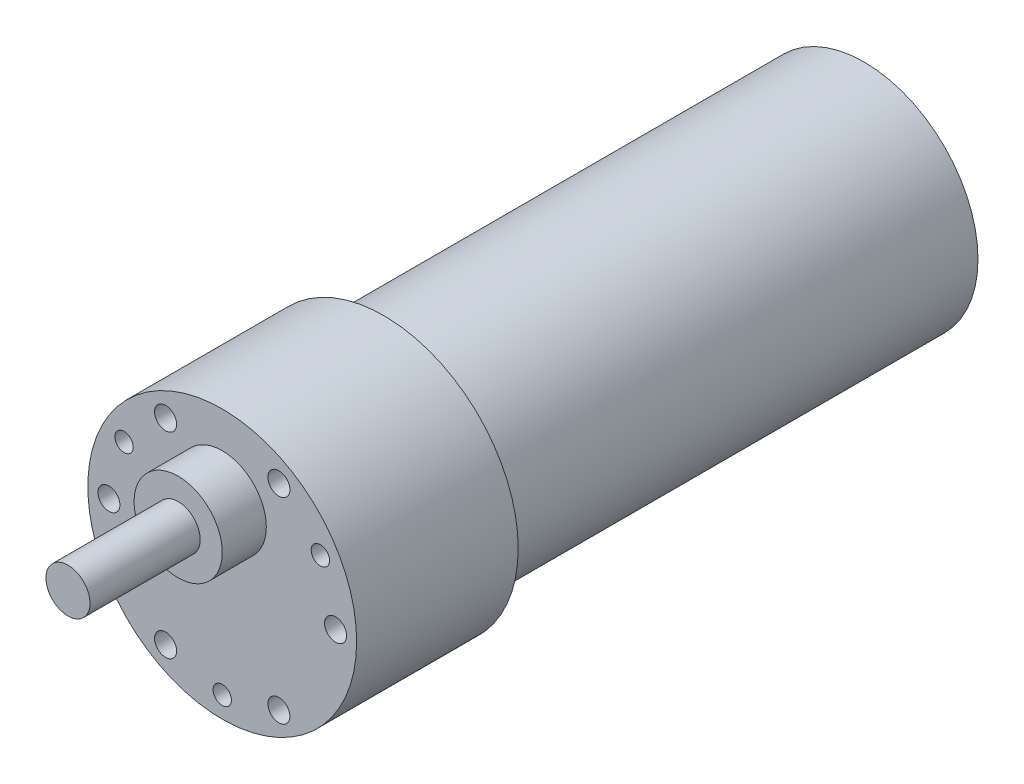
SolidWorks part; units mm, degrees
ref_plane "Alzado" through (0, 0, 0) normal (0, 0, 1) x (1, 0, 0)
ref_plane "Planta" through (0, 0, 0) normal (0, 1, 0) x (1, 0, 0)
ref_plane "Vista lateral" through (0, 0, 0) normal (1, 0, 0) x (0, 0, -1)
sketch "Croquis1" plane through (0, 0, 0) normal (0, 0, 1) x (1, 0, 0)
  circle A0 centre (0, 0) radius 15.5
  dimension "D1" = 31
extrude "Saliente-Extruir1" add sketch "Croquis1" along normal blind 65.4
sketch "Croquis2" plane through (0, 0, 0) normal (0, 0, -1) x (-1, 0, 0)
  circle A0 centre (0, 0) radius 6
  dimension "D1" = 12
extrude "Saliente-Extruir2" add sketch "Croquis2" along normal blind 2
sketch "Croquis3" plane through (0, 0, 65.4) normal (0, 0, 1) x (1, 0, 0)
  circle A0 centre (0, 0) radius 18.3
  dimension "D1" = 36.6
extrude "Saliente-Extruir3" add sketch "Croquis3" along normal blind 22
sketch "Croquis4" plane through (0, 0, 87.4) normal (0, 0, 1) x (1, 0, 0)
  circle A0 centre (0, 0) radius 16.93
  circle A1 centre (0, 0) radius 18.3 construction
  circle A2 centre (-15.43, 0) radius 1.5
  circle A3 centre (-7.715, 13.3628) radius 1.5
  circle A4 centre (7.715, 13.3628) radius 1.5
  circle A5 centre (15.43, 0) radius 1.5
  circle A6 centre (7.715, -13.3628) radius 1.5
  circle A7 centre (-7.715, -13.3628) radius 1.5
  point P19 (0, 0)
  dimension "D1" = 1.37
  dimension "D2" = 3
  dimension "D3" = 6
extrude "Cortar-Extruir1" cut sketch "Croquis4" against normal blind 20 contours A2 | A3 | A4 | A5 | A7 | A6
sketch "Croquis5" plane through (0, 0, 87.4) normal (0, 0, 1) x (1, 0, 0)
  circle A0 centre (0, 0) radius 15.43
  circle A1 centre (0, -15.43) radius 1.25
  circle A2 centre (-13.3628, 7.715) radius 1.25
  circle A3 centre (13.3628, 7.715) radius 1.25
  point P12 (0, 0)
  dimension "D1" = 2.5
  dimension "D2" = 3
extrude "Cortar-Extruir2" cut sketch "Croquis5" against normal blind 20 contours A1 | A2 | A3
sketch "Croquis6" plane through (0, 0, 87.4) normal (0, 0, 1) x (1, 0, 0)
  line L0 (0, -15.43) -> (0, 7.37) construction
  circle A0 centre (0, 7.37) radius 6
  dimension "D2" = 12
  dimension "D1" = 22.8
extrude "Saliente-Extruir4" add sketch "Croquis6" along normal blind 6
sketch "Croquis7" plane through (0, 0, 93.4) normal (0, 0, 1) x (1, 0, 0)
  circle A0 centre (0, 7.37) radius 3
  dimension "D1" = 6
extrude "Saliente-Extruir5" add sketch "Croquis7" along normal blind 15
